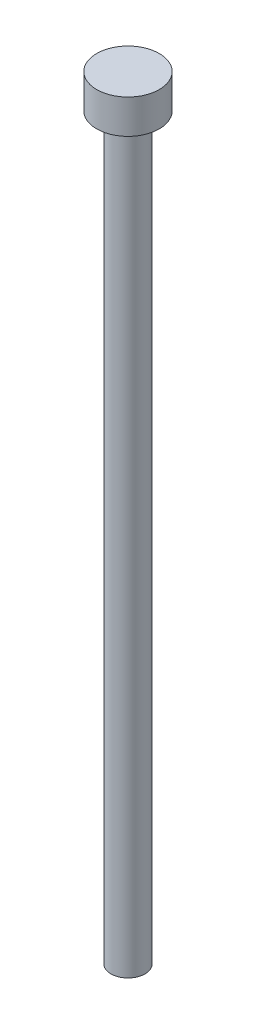
SolidWorks part; units mm, degrees
ref_plane "Front Plane" through (0, 0, 0) normal (0, 0, 1) x (1, 0, 0)
ref_plane "Top Plane" through (0, 0, 0) normal (0, 1, 0) x (1, 0, 0)
ref_plane "Right Plane" through (0, 0, 0) normal (1, 0, 0) x (0, 0, -1)
sketch "Sketch1" plane through (0, 0, 0) normal (0, 1, 0) x (1, 0, 0)
  circle A0 centre (0, 0) radius 3
  dimension "D1" = 6
extrude "Boss-Extrude1" add sketch "Sketch1" against normal blind 130
sketch "Sketch2" plane through (0, 0, 0) normal (0, 1, 0) x (1, 0, 0)
  circle A0 centre (0, 0) radius 5.5
  dimension "D1" = 11
extrude "Boss-Extrude2" add sketch "Sketch2" along normal blind 6
